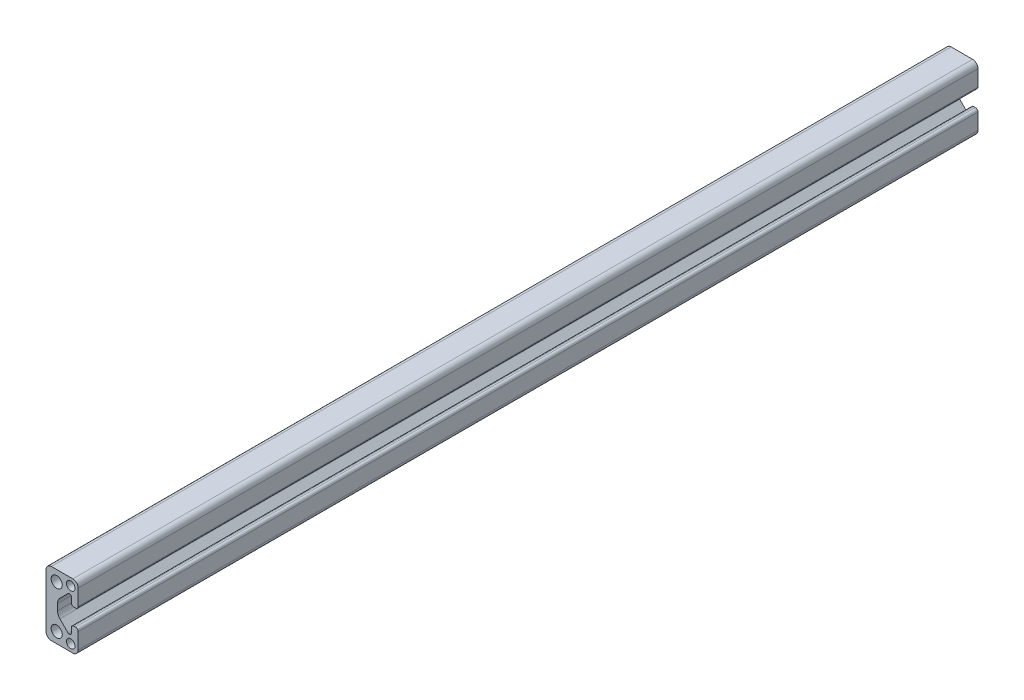
SolidWorks part; units mm, degrees
ref_plane "Front Plane" through (0, 0, 0) normal (0, 0, 1) x (1, 0, 0)
ref_plane "Top Plane" through (0, 0, 0) normal (0, 1, 0) x (1, 0, 0)
ref_plane "Right Plane" through (0, 0, 0) normal (1, 0, 0) x (0, 0, -1)
sketch "Sketch1" plane through (0, 0, 0) normal (0, 0, 1) x (1, 0, 0)
  line L0 (-6.35, 0) -> (6.35, 0) construction
  line L1 (6.35, 4.3011) -> (6.35, 10.5833)
  line L2 (4.2333, 12.7) -> (-4.2333, 12.7)
  line L3 (-6.35, 10.5833) -> (-6.35, 0)
  line L4 (-1.778, 0) -> (-1.778, 1.27)
  line L5 (-0.8467, 3.5339) -> (2.4133, 6.7939)
  line L6 (2.7725, 6.9427) -> (3.048, 6.9427)
  line L7 (3.6407, 6.35) -> (3.6407, 4.3011)
  line L8 (4.6905, 3.2512) -> (5.3001, 3.2512)
  circle A2 centre (3.429, 9.906) radius 1.6933
  circle A3 centre (-2.1167, 8.4667) radius 2.2013
  arc A4 (6.35, 10.5833) -> (4.2333, 12.7) centre (4.2333, 10.5833) ccw
  arc A5 (-4.2333, 12.7) -> (-6.35, 10.5833) centre (-4.2333, 10.5833) ccw
  arc A6 (-0.8467, 3.5339) -> (-1.778, 1.27) centre (1.4393, 1.27) ccw
  arc A7 (2.7725, 6.9427) -> (2.4133, 6.7939) centre (2.7725, 6.4347) ccw
  arc A8 (3.6407, 6.35) -> (3.048, 6.9427) centre (3.048, 6.35) ccw
  arc A9 (3.6407, 4.3011) -> (4.6905, 3.2512) centre (4.6905, 4.3011) ccw
  arc A10 (5.3001, 3.2512) -> (6.35, 4.3011) centre (5.3001, 4.3011) ccw
  dimension "D8" = 2.1167
  dimension "D9" = 3.3867
  dimension "D10" = 4.4027
  dimension "D13" = 1.0499
  dimension "D14" = 3.2173
  dimension "D16" = 0.508
  dimension "D17" = 0.5927
  dimension "Rail Height" = 25.4
  dimension "Rail Width" = 12.7
  dimension "D1" = 4.572
  dimension "D2" = 135
  dimension "D3" = 1.27
  dimension "D4" = 16.9333
  dimension "D5" = 4.2333
  dimension "D7" = 2.921
  dimension "D6" = 19.812
  dimension "TSlot Wdith" = 6.5024
  dimension "D11" = 2.7093
  dimension "D12" = 6.9427
  dimension "D15" = 5.5033
sketch "Sketch2" plane through (0, 0, 0) normal (1, 0, 0) x (0, 0, -1)
  line L0 (-914.4, 0) -> (914.4, 0)
  point P2 (-876.3, 0)
  point P3 (876.3, 0)
  dimension "Length" = 1828.8
  dimension "D1" = 38.1
  dimension "D2" = 38.1
sketch "Sketch3" plane through (0, 0, 0) normal (0, 0, 1) x (1, 0, 0)
  line L0 (-1.778, 0) -> (-1.778, 1.27) construction
  line L1 (-0.8467, 3.5339) -> (2.4133, 6.7939) construction
  line L2 (2.7725, 6.9427) -> (3.048, 6.9427) construction
  line L3 (3.6407, 6.35) -> (3.6407, 4.3011) construction
  line L4 (4.6905, 3.2512) -> (5.3001, 3.2512) construction
  line L5 (6.35, 4.3011) -> (6.35, 10.5833) construction
  line L6 (4.2333, 12.7) -> (-4.2333, 12.7) construction
  line L7 (-6.35, 10.5833) -> (-6.35, 0) construction
  line L8 (-1.778, 0) -> (-1.778, 1.27)
  line L9 (-0.8467, 3.5339) -> (2.4133, 6.7939)
  line L10 (2.7725, 6.9427) -> (3.048, 6.9427)
  line L11 (3.6407, 6.35) -> (3.6407, 4.3011)
  line L12 (4.6905, 3.2512) -> (5.3001, 3.2512)
  line L13 (6.35, 4.3011) -> (6.35, 10.5833)
  line L14 (4.2333, 12.7) -> (-4.2333, 12.7)
  line L15 (-6.35, 10.5833) -> (-6.35, 0)
  line L16 (-6.35, 0) -> (-1.778, 0)
  arc A0 (-0.8467, 3.5339) -> (-1.778, 1.27) centre (1.4393, 1.27) ccw construction
  circle A1 centre (-2.1167, 8.4667) radius 2.2013
  circle A2 centre (-2.1167, 8.4667) radius 2.2013
  circle A3 centre (3.429, 9.906) radius 1.6933
  circle A4 centre (3.429, 9.906) radius 1.6933
  arc A5 (2.7725, 6.9427) -> (2.4133, 6.7939) centre (2.7725, 6.4347) ccw construction
  arc A6 (3.6407, 6.35) -> (3.048, 6.9427) centre (3.048, 6.35) ccw construction
  arc A7 (3.6407, 4.3011) -> (4.6905, 3.2512) centre (4.6905, 4.3011) ccw construction
  arc A8 (5.3001, 3.2512) -> (6.35, 4.3011) centre (5.3001, 4.3011) ccw construction
  arc A9 (6.35, 10.5833) -> (4.2333, 12.7) centre (4.2333, 10.5833) ccw construction
  arc A10 (-4.2333, 12.7) -> (-6.35, 10.5833) centre (-4.2333, 10.5833) ccw construction
  arc A11 (-0.8467, 3.5339) -> (-1.778, 1.27) centre (1.4393, 1.27) ccw
  arc A12 (2.7725, 6.9427) -> (2.4133, 6.7939) centre (2.7725, 6.4347) ccw
  arc A13 (3.6407, 6.35) -> (3.048, 6.9427) centre (3.048, 6.35) ccw
  arc A14 (3.6407, 4.3011) -> (4.6905, 3.2512) centre (4.6905, 4.3011) ccw
  arc A15 (5.3001, 3.2512) -> (6.35, 4.3011) centre (5.3001, 4.3011) ccw
  arc A16 (6.35, 10.5833) -> (4.2333, 12.7) centre (4.2333, 10.5833) ccw
  arc A17 (-4.2333, 12.7) -> (-6.35, 10.5833) centre (-4.2333, 10.5833) ccw
  dimension "D1" = 0
  dimension "D2" = 0
extrude "Boss-Extrude1" add sketch "Sketch3" along normal mid plane 1828.8
mirror "Mirror1" about plane through (0, 0, 0) normal (0, 1, 0) of bodies 104
sketch "Sketch4" plane through (-6.35, 0, 0) normal (-1, 0, 0) x (0, 0, 1)
  line L0 (914.4, 0) -> (-914.4, 0) construction
  line L1 (914.4, 10.5833) -> (914.4, -10.5833) construction
  line L2 (-914.4, 10.5833) -> (-914.4, -10.5833) construction
  circle A0 centre (889, 0) radius 9.525
  dimension "D1" = 19.05
  dimension "D2" = 25.4
sketch "Sketch5" plane through (0, 0, 914.4) normal (0, 0, 1) x (1, 0, 0)
  line L14 (-6.35, 10.5833) -> (-6.35, -10.5833)
  line L15 (-4.2333, -12.7) -> (4.2333, -12.7)
  line L16 (6.35, -10.5833) -> (6.35, -4.3011)
  line L17 (5.3001, -3.2512) -> (4.6905, -3.2512)
  line L18 (3.6407, -4.3011) -> (3.6407, -6.35)
  line L19 (3.048, -6.9427) -> (2.7725, -6.9427)
  line L20 (2.4133, -6.7939) -> (-0.8467, -3.5339)
  line L21 (-1.778, -1.27) -> (-1.778, 1.27)
  line L22 (-0.8467, 3.5339) -> (2.4133, 6.7939)
  line L23 (2.7725, 6.9427) -> (3.048, 6.9427)
  line L24 (3.6407, 6.35) -> (3.6407, 4.3011)
  line L25 (4.6905, 3.2512) -> (5.3001, 3.2512)
  line L26 (6.35, 4.3011) -> (6.35, 10.5833)
  line L27 (4.2333, 12.7) -> (-4.2333, 12.7)
  line L28 (-6.35, 10.5833) -> (-6.35, -10.5833)
  line L29 (-4.2333, -12.7) -> (4.2333, -12.7)
  line L30 (6.35, -10.5833) -> (6.35, -4.3011)
  line L31 (5.3001, -3.2512) -> (4.6905, -3.2512)
  line L32 (3.6407, -4.3011) -> (3.6407, -6.35)
  line L33 (3.048, -6.9427) -> (2.7725, -6.9427)
  line L34 (2.4133, -6.7939) -> (-0.8467, -3.5339)
  line L35 (-1.778, -1.27) -> (-1.778, 1.27)
  line L36 (-0.8467, 3.5339) -> (2.4133, 6.7939)
  line L37 (2.7725, 6.9427) -> (3.048, 6.9427)
  line L38 (3.6407, 6.35) -> (3.6407, 4.3011)
  line L39 (4.6905, 3.2512) -> (5.3001, 3.2512)
  line L40 (6.35, 4.3011) -> (6.35, 10.5833)
  line L41 (4.2333, 12.7) -> (-4.2333, 12.7)
  arc A14 (-6.35, -10.5833) -> (-4.2333, -12.7) centre (-4.2333, -10.5833) ccw
  arc A15 (4.2333, -12.7) -> (6.35, -10.5833) centre (4.2333, -10.5833) ccw
  arc A16 (6.35, -4.3011) -> (5.3001, -3.2512) centre (5.3001, -4.3011) ccw
  arc A17 (4.6905, -3.2512) -> (3.6407, -4.3011) centre (4.6905, -4.3011) ccw
  arc A18 (3.048, -6.9427) -> (3.6407, -6.35) centre (3.048, -6.35) ccw
  arc A19 (2.4133, -6.7939) -> (2.7725, -6.9427) centre (2.7725, -6.4347) ccw
  arc A20 (-1.778, -1.27) -> (-0.8467, -3.5339) centre (1.4393, -1.27) ccw
  arc A21 (-0.8467, 3.5339) -> (-1.778, 1.27) centre (1.4393, 1.27) ccw
  arc A22 (2.7725, 6.9427) -> (2.4133, 6.7939) centre (2.7725, 6.4347) ccw
  arc A23 (3.6407, 6.35) -> (3.048, 6.9427) centre (3.048, 6.35) ccw
  arc A24 (3.6407, 4.3011) -> (4.6905, 3.2512) centre (4.6905, 4.3011) ccw
  arc A25 (5.3001, 3.2512) -> (6.35, 4.3011) centre (5.3001, 4.3011) ccw
  arc A26 (6.35, 10.5833) -> (4.2333, 12.7) centre (4.2333, 10.5833) ccw
  arc A27 (-4.2333, 12.7) -> (-6.35, 10.5833) centre (-4.2333, 10.5833) ccw
  arc A28 (-6.35, -10.5833) -> (-4.2333, -12.7) centre (-4.2333, -10.5833) ccw
  arc A29 (4.2333, -12.7) -> (6.35, -10.5833) centre (4.2333, -10.5833) ccw
  arc A30 (6.35, -4.3011) -> (5.3001, -3.2512) centre (5.3001, -4.3011) ccw
  arc A31 (4.6905, -3.2512) -> (3.6407, -4.3011) centre (4.6905, -4.3011) ccw
  arc A32 (3.048, -6.9427) -> (3.6407, -6.35) centre (3.048, -6.35) ccw
  arc A33 (2.4133, -6.7939) -> (2.7725, -6.9427) centre (2.7725, -6.4347) ccw
  arc A34 (-1.778, -1.27) -> (-0.8467, -3.5339) centre (1.4393, -1.27) ccw
  arc A35 (-0.8467, 3.5339) -> (-1.778, 1.27) centre (1.4393, 1.27) ccw
  arc A36 (2.7725, 6.9427) -> (2.4133, 6.7939) centre (2.7725, 6.4347) ccw
  arc A37 (3.6407, 6.35) -> (3.048, 6.9427) centre (3.048, 6.35) ccw
  arc A38 (3.6407, 4.3011) -> (4.6905, 3.2512) centre (4.6905, 4.3011) ccw
  arc A39 (5.3001, 3.2512) -> (6.35, 4.3011) centre (5.3001, 4.3011) ccw
  arc A40 (6.35, 10.5833) -> (4.2333, 12.7) centre (4.2333, 10.5833) ccw
  arc A41 (-4.2333, 12.7) -> (-6.35, 10.5833) centre (-4.2333, 10.5833) ccw
  dimension "D1" = 0
extrude "Cut-Extrude1" cut sketch "Sketch5" against normal blind 1473.2
sketch "Sketch6" plane through (-1.778, 0, 0) normal (1, 0, 0) x (0, 0, -1)
  line L0 (-914.4, 0) -> (914.4, 0) construction
  line L1 (736.6, -12.7) -> (736.6, 12.7) construction
  line L2 (558.8, -12.7) -> (914.4, -12.7) construction
  line L3 (558.8, 12.7) -> (914.4, 12.7) construction
  circle A0 centre (901.7, 0) radius 3
  circle A1 centre (571.5, 0) radius 3
  dimension "D1" = 6
  dimension "D2" = 12.7
  dimension "D3" = 177.8
extrude "Cut-Extrude2" cut sketch "Sketch6" against normal through all both and the other way through all contours A0 | A1
equation "\"D1@Sketch1\"=\"Rail Width@Sketch1\"*0.36"
equation "\"D3@Sketch1\"=\"Rail Height@Sketch1\"*0.05"
equation "\"D4@Sketch1\"=\"Rail Height@Sketch1\"*2/3"
equation "\"D5@Sketch1\"=\"D4@Sketch1\"*1/4"
equation "\"D7@Sketch1\"=\"Rail Width@Sketch1\"*0.23"
equation "\"D6@Sketch1\"=\"Rail Height@Sketch1\"*0.78"
equation "\"D8@Sketch1\"=\"D4@Sketch1\"*1/8"
equation "\"D9@Sketch1\"=\"D4@Sketch1\"*1/5"
equation "\"D10@Sketch1\"=\"D4@Sketch1\"*0.26"
equation "\"D11@Sketch1\"=\"D4@Sketch1\"*0.16"
equation "\"D12@Sketch1\"=\"D4@Sketch1\"*0.41"
equation "\"D13@Sketch1\"=\"D4@Sketch1\"*0.062"
equation "\"D14@Sketch1\"=\"D9@Sketch1\"*0.95"
equation "\"D15@Sketch1\"=\"D4@Sketch1\"*0.325"
equation "\"D16@Sketch1\"=\"D4@Sketch1\"*0.03"
equation "\"D17@Sketch1\"=\"D4@Sketch1\"*0.035"
equation "\"D2@Sketch2\"=\"D1@Sketch2\""
equation "\"D1@Boss-Extrude1\"=\"length@sketch2\""
